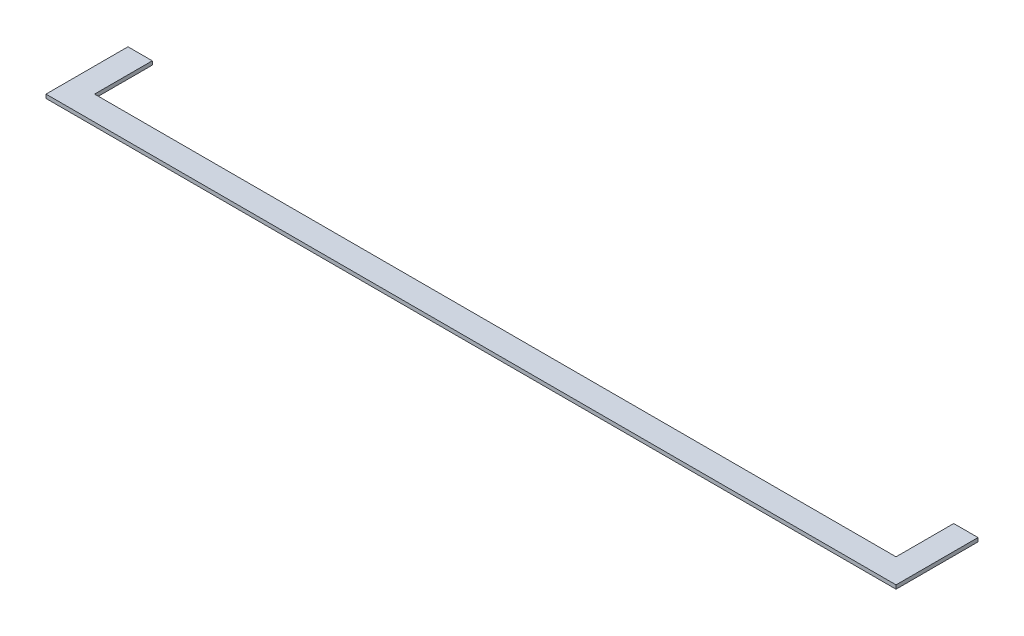
SolidWorks part; units mm, degrees
ref_plane "Front Plane" through (0, 0, 0) normal (0, 0, 1) x (1, 0, 0)
ref_plane "Top Plane" through (0, 0, 0) normal (0, 1, 0) x (1, 0, 0)
ref_plane "Right Plane" through (0, 0, 0) normal (1, 0, 0) x (0, 0, -1)
sketch "Sketch1" plane through (0, 0, 0) normal (0, 1, 0) x (1, 0, 0)
  line L1 (0, 0) -> (280, 0)
  line L2 (0, 0) -> (0, 27)
  line L3 (0, 27) -> (8, 27)
  line L4 (280, 0) -> (280, 27)
  line L6 (8, 8) -> (272, 8)
  line L8 (8, 19) -> (272, 19) construction
  line L9 (272, 8) -> (272, 19) construction
  line L10 (8, 8) -> (8, 19) construction
  line L11 (8, 8) -> (8, 27)
  line L12 (272, 8) -> (272, 27)
  line L13 (272, 27) -> (280, 27)
  line L15 (0, 27) -> (280, 27) construction
  dimension "D1" = 280
  dimension "D2" = 27
  dimension "D3" = 8
extrude "Boss-Extrude1" add sketch "Sketch1" along normal blind 1.25
